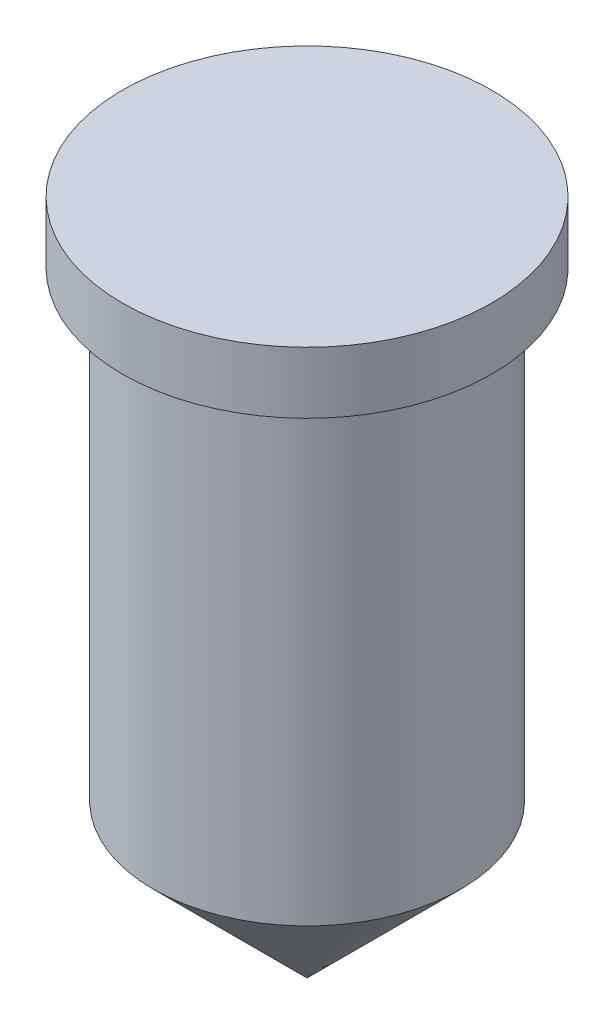
SolidWorks part; units mm, degrees
ref_plane "Płaszczyzna przednia" through (0, 0, 0) normal (0, 0, 1) x (1, 0, 0)
ref_plane "Płaszczyzna górna" through (0, 0, 0) normal (0, 1, 0) x (1, 0, 0)
ref_plane "Płaszczyzna prawa" through (0, 0, 0) normal (1, 0, 0) x (0, 0, -1)
sketch "Szkic1" plane through (0, 0, 0) normal (0, 1, 0) x (1, 0, 0)
  circle A0 centre (0, 0) radius 2.5
  dimension "D1" = 5
extrude "Dodanie-wyciągnięcie1" add sketch "Szkic1" along normal blind 10
chamfer "Sfazowanie1" distance 2.5 angle 45 1 edges at (0, 0, 2.5)
sketch "Szkic3" plane through (0, 10, 0) normal (0, 1, 0) x (1, 0, 0)
  circle A2 centre (0, 0) radius 3
  circle A3 centre (0, 0) radius 3
  dimension "D1" = 0.5
extrude "Dodanie-wyciągnięcie2" add sketch "Szkic3" along normal blind 1 contours A3
